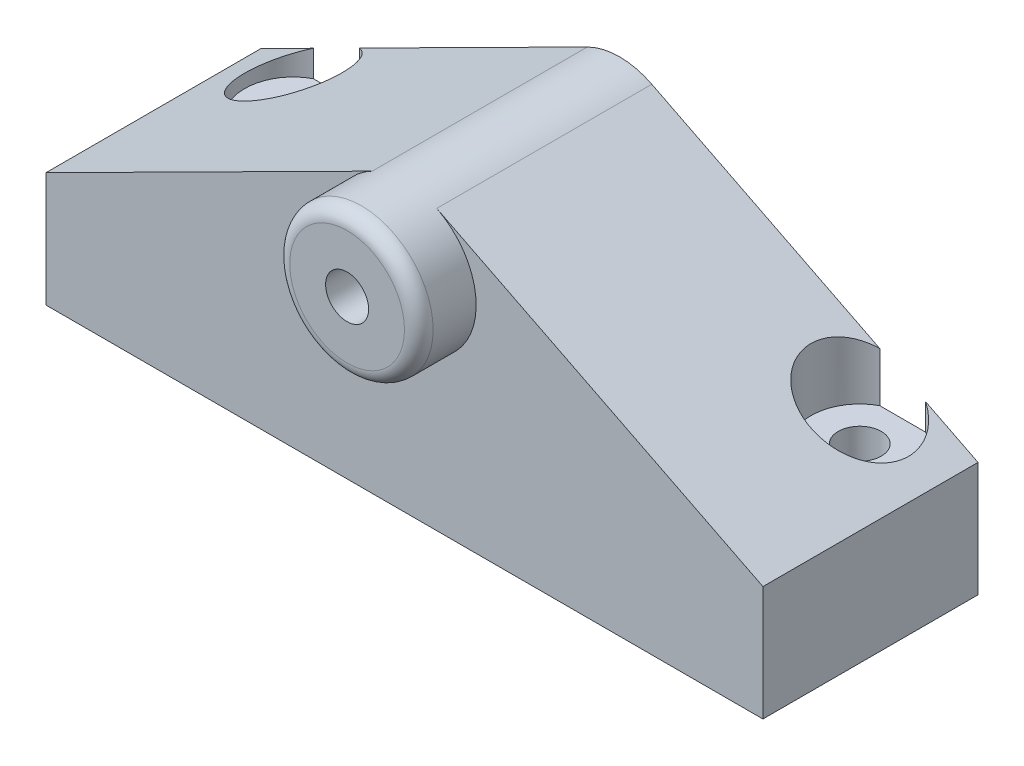
SolidWorks part; units mm, degrees
ref_plane "Front" through (0, 0, 0) normal (0, 0, 1) x (1, 0, 0)
ref_plane "Top" through (0, 0, 0) normal (0, 1, 0) x (1, 0, 0)
ref_plane "Right" through (0, 0, 0) normal (1, 0, 0) x (0, 0, -1)
sketch "草图1" plane through (0, 0, 0) normal (0, 0, 1) x (1, 0, 0)
  line L0 (0, 0) -> (50, 0)
  line L2 (0, 0) -> (0, 8)
  line L3 (0, 8) -> (22.7498, 19.465)
  line L4 (50, 0) -> (50, 8)
  line L5 (50, 8) -> (27.2502, 19.465)
  arc A0 (27.2502, 19.465) -> (22.7498, 19.465) centre (25, 15) ccw
  circle A1 centre (25, 15) radius 1.5
extrude "凸台-拉伸1" add sketch "草图1" along normal blind 15
sketch "草图2" plane through (0, 0, 15) normal (0, 0, 1) x (1, 0, 0)
  circle A0 centre (25, 15) radius 5
  circle A1 centre (25, 15) radius 1.5
extrude "凸台-拉伸2" add sketch "草图2" along normal blind 4
fillet "圆角1" radius 1 1 edges at (30, 15, 19)
sketch "草图3" plane through (0, 0, 0) normal (0, -1, 0) x (1, 0, 0)
  circle A1 centre (5.25, 3) radius 1.5
  circle A2 centre (44.75, 3) radius 1.5
extrude "切除-拉伸1" cut sketch "草图3" against normal blind 19
ref_plane "基准面1" through (0, 8, 0) normal (0, -1, 0) x (-1, 0, 0)
sketch "草图4" plane through (0, 8, 0) normal (0, -1, 0) x (-1, 0, 0)
  circle A0 centre (-44.75, -3) radius 3.4
  circle A1 centre (-5.25, -3) radius 3.4
extrude "切除-拉伸3" cut sketch "草图4" against normal blind 19 contours A0 | A1
